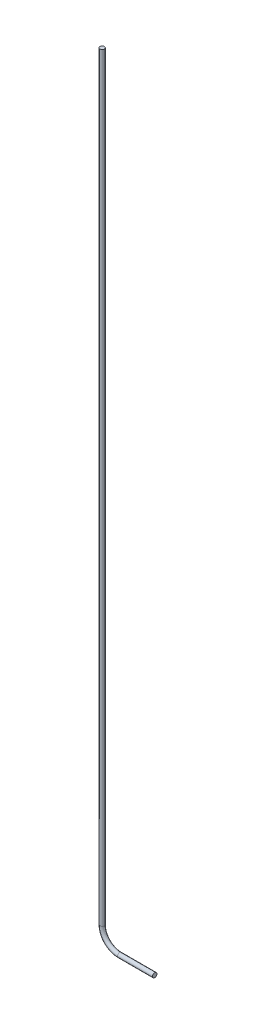
SolidWorks part; units mm, degrees
ref_plane "Front Plane" through (0, 0, 0) normal (0, 0, 1) x (1, 0, 0)
ref_plane "Top Plane" through (0, 0, 0) normal (0, 1, 0) x (1, 0, 0)
ref_plane "Right Plane" through (0, 0, 0) normal (1, 0, 0) x (0, 0, -1)
sketch "Sketch1" plane through (0, 0, 0) normal (0, 0, 1) x (1, 0, 0)
  line L0 (0, 50.8) -> (0, 2253.996)
  line L1 (50.8, 0) -> (152.4, 0)
  arc A0 (50.8, 0) -> (0, 50.8) centre (50.8, 50.8) cw
  point P6 (0, 0)
  dimension "D2" = 50.8
  dimension "D1" = 152.4
  dimension "Length from Tank Model" = 2253.996
sweep "Sweep1" add path "Sketch1" circular profile diameter 12.7 parameters "D3"=12.7
equation "\"rebar diameter\"= .5"
equation "\"D3@Sweep1\"=\"rebar diameter\""
